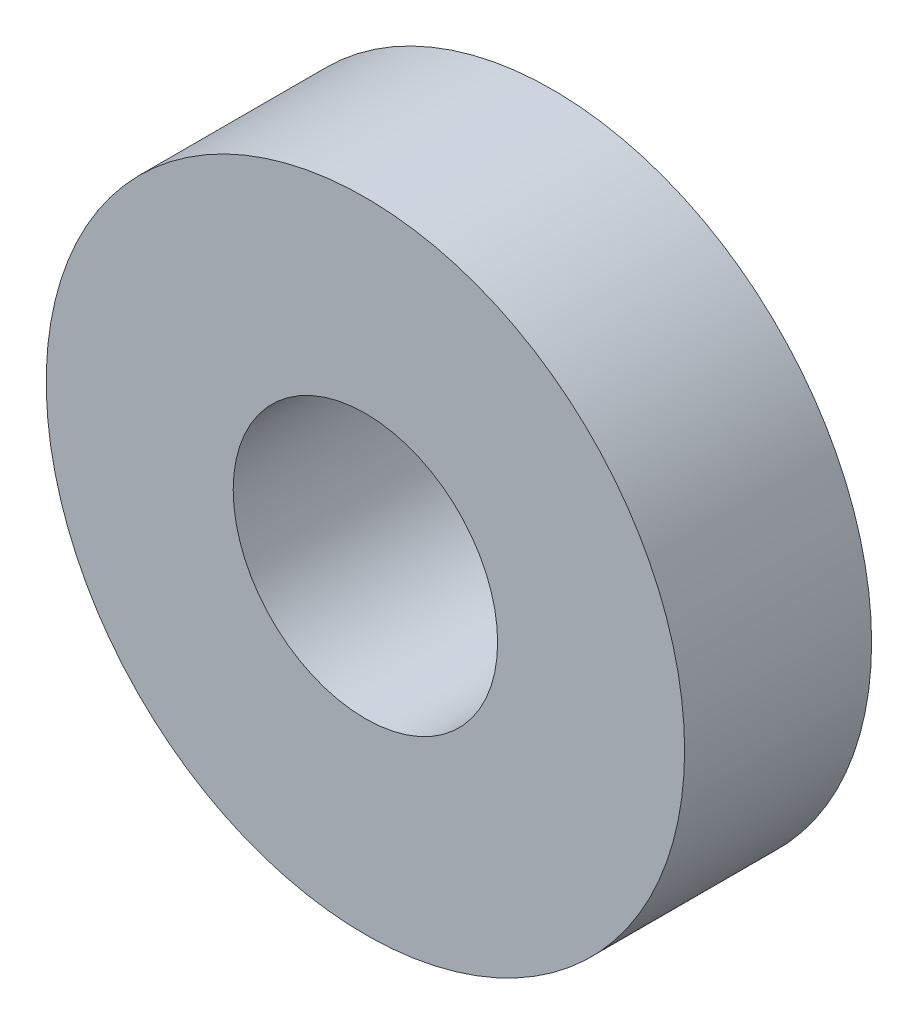
SolidWorks part; units mm, degrees
ref_plane "Front Plane" through (0, 0, 0) normal (0, 0, 1) x (1, 0, 0)
ref_plane "Top Plane" through (0, 0, 0) normal (0, 1, 0) x (1, 0, 0)
ref_plane "Right Plane" through (0, 0, 0) normal (1, 0, 0) x (0, 0, -1)
sketch "Sketch1" plane through (0, 0, 0) normal (0, 0, 1) x (1, 0, 0)
  circle A0 centre (0, 0) radius 10.84
  dimension "D1" = 21.68
extrude "Boss-Extrude1" add sketch "Sketch1" along normal blind 6.35
sketch "Sketch4" plane through (0, 0, 6.35) normal (0, 0, 1) x (1, 0, 0)
  line L0 (0, 4.4901) -> (-4.4901, 0)
  line L1 (0, 4.4901) -> (4.4901, 0)
  line L2 (-4.4901, 0) -> (0, -4.4901)
  line L3 (4.4901, 0) -> (0, -4.4901)
  line L4 (4.4901, 0) -> (10.84, 0) construction
  circle A0 centre (0, 0) radius 4.4901
  circle A1 centre (0, 0) radius 10.84 construction
  dimension "D2" = 6.3499
extrude "Cut-Extrude1" cut sketch "Sketch4" against normal through all contours A0
